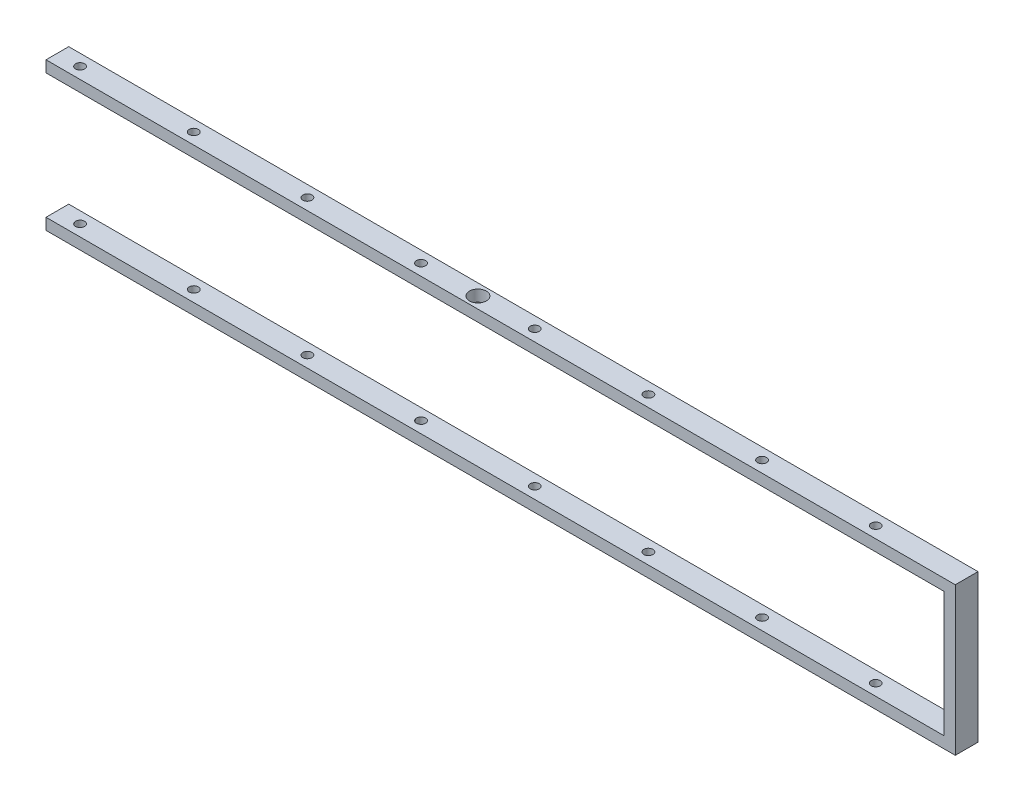
SolidWorks part; units mm, degrees
ref_plane "Plan de face" through (0, 0, 0) normal (0, 0, 1) x (1, 0, 0)
ref_plane "Plan de dessus" through (0, 0, 0) normal (0, 1, 0) x (1, 0, 0)
ref_plane "Plan de droite" through (0, 0, 0) normal (1, 0, 0) x (0, 0, -1)
sketch "Esquisse1" plane through (0, 0, 0) normal (0, 0, 1) x (1, 0, 0)
  line L0 (0, 120) -> (790, 120)
  line L1 (0, 0) -> (800, 0)
  line L2 (0, 0) -> (0, 130)
  line L3 (0, 130) -> (800, 130)
  line L4 (800, 0) -> (800, 130)
  line L9 (790, 10) -> (790, 120)
  line L10 (0, 10) -> (790, 10)
  dimension "D1" = 130
  dimension "D2" = 10
  dimension "D4" = 800
extrude "Boss.-Extru.1" add sketch "Esquisse1" along normal blind 20 contours L10 L2 L1 L4 L3 L0 L9
sketch "Esquisse2" plane through (0, 130, 0) normal (0, 1, 0) x (1, 0, 0)
  line L1 (0, -10) -> (800, -10) construction
  line L2 (0, -20) -> (0, 0) construction
  line L3 (800, -20) -> (800, 0) construction
  circle A0 centre (20, -10) radius 4
  dimension "D1" = 8
  dimension "D2" = 20
extrude "Enlèv. mat.-Extru.1" cut sketch "Esquisse2" against normal through all
pattern_linear "Répétition linéaire1" count 8 spacing 100 along (1, 0, 0) of "Enlèv. mat.-Extru.1"
sketch "Esquisse3" plane through (0, 130, 0) normal (0, 1, 0) x (1, 0, 0)
  line L0 (0, -20) -> (0, 0) construction
  line L2 (800, -20) -> (800, 0) construction
  circle A0 centre (370, -10) radius 7.5
  point P8 (0, 0)
  point P11 (800, -10)
  dimension "D1" = 15
  dimension "D2" = 370
extrude "Enlèv. mat.-Extru.2" cut sketch "Esquisse3" against normal blind 10
